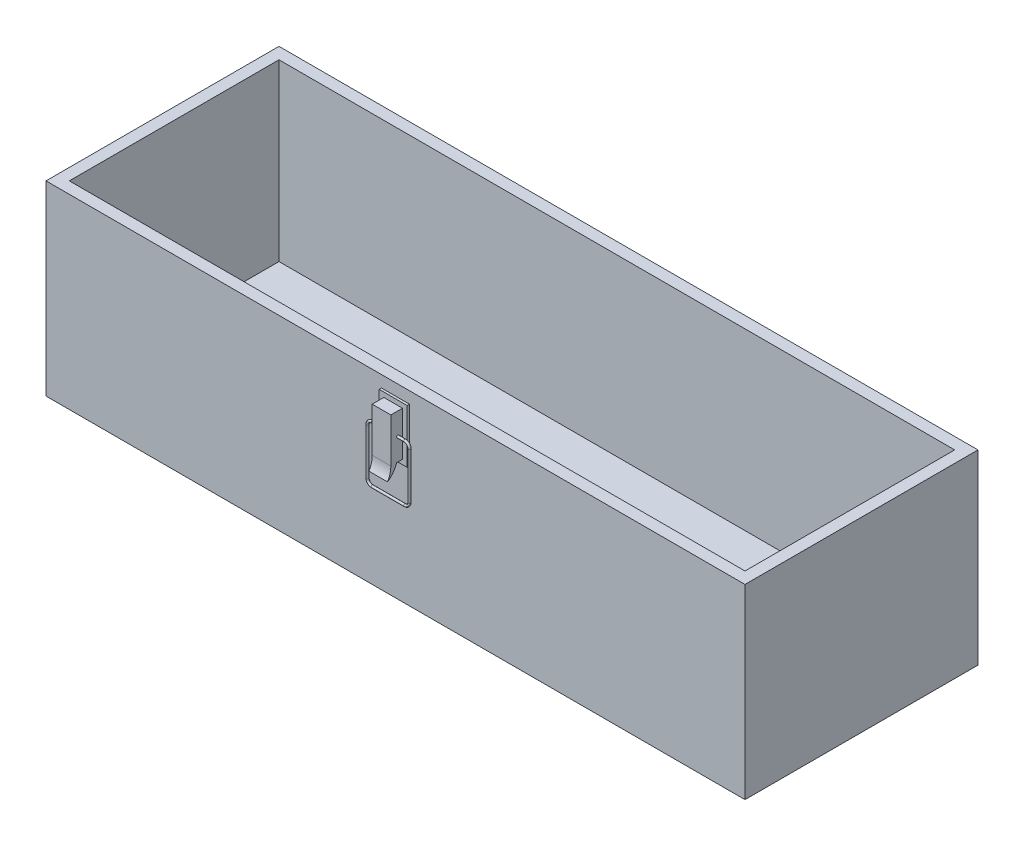
SolidWorks part; units mm, degrees
ref_plane "Front Plane" through (0, 0, 0) normal (0, 0, 1) x (1, 0, 0)
ref_plane "Top Plane" through (0, 0, 0) normal (0, 1, 0) x (1, 0, 0)
ref_plane "Right Plane" through (0, 0, 0) normal (1, 0, 0) x (0, 0, -1)
sketch "Sketch1" plane through (0, 0, 0) normal (0, 1, 0) x (1, 0, 0)
  line L1 (-150, -50) -> (150, -50)
  line L2 (-150, -50) -> (-150, 50)
  line L3 (-150, 50) -> (150, 50)
  line L4 (150, -50) -> (150, 50)
  line L5 (-150, -50) -> (150, 50) construction
  line L6 (-150, 50) -> (150, -50) construction
  point P0 (0, 0)
  dimension "D1" = 300
  dimension "D2" = 100
extrude "Boss-Extrude1" add sketch "Sketch1" along normal blind 80
shell "Shell1" thickness 5
sketch "Sketch2" plane through (0, 0, 50) normal (0, 0, 1) x (1, 0, 0)
  line L0 (0, 0) -> (0, 63.5) construction
  line L1 (-6, 75) -> (6, 75)
  line L2 (-6, 75) -> (-6, 52)
  line L3 (-6, 52) -> (6, 52)
  line L4 (6, 75) -> (6, 52)
  line L5 (-6, 75) -> (6, 52) construction
  line L6 (-6, 52) -> (6, 75) construction
  line L7 (-150, 0) -> (150, 0) construction
  line L8 (-150, 80) -> (150, 80) construction
  point P0 (0, 63.5)
  dimension "D1" = 12
  dimension "D2" = 23
  dimension "D3" = 5
extrude "Boss-Extrude2" add sketch "Sketch2" along normal blind 1
sketch "Sketch3" plane through (0, 0, 51) normal (0, 0, 1) x (1, 0, 0)
  line L8 (4, 54) -> (4, 73)
  line L9 (-4, 54) -> (4, 54)
  line L10 (-4, 73) -> (-4, 54)
  line L11 (4, 73) -> (-4, 73)
  line L12 (4, 54) -> (4, 73)
  line L13 (-4, 54) -> (4, 54)
  line L14 (-4, 73) -> (-4, 54)
  line L15 (4, 73) -> (-4, 73)
  dimension "D1" = 2
extrude "Boss-Extrude3" add sketch "Sketch3" along normal blind 5
sketch "Sketch4" plane through (4, 0, 0) normal (1, 0, 0) x (0, 0, -1)
  line L0 (-56, 54) -> (-56, 73) construction
  line L1 (-56, 54) -> (-51, 54) construction
  line L2 (-56, 54) -> (-53.5, 54)
  arc A0 (-56, 54) -> (-57.3951, 48.7908) centre (-66.4233, 54) cw
  arc A1 (-53.5, 54) -> (-57.3951, 48.7908) centre (-63.3786, 57.3256) cw
extrude "Boss-Extrude4" add sketch "Sketch4" against normal up to surface (8 mm away) up to face at (-4, 63.5, 53.5)
ref_plane "Plane1" through (0, 0, 53) normal (0, 0, 1) x (1, 0, 0)
sketch "Sketch5" plane through (0, 0, 53) normal (0, 0, 1) x (1, 0, 0)
  line L0 (-4, 63.5) -> (-7, 63.5)
  line L1 (-4, 73) -> (-4, 54) construction
  line L2 (-9, 61.5) -> (-9, 41.5)
  line L3 (-7, 39.5) -> (7, 39.5)
  line L4 (9, 41.5) -> (9, 61.5)
  line L5 (7, 63.5) -> (4, 63.5)
  line L6 (4, 54) -> (4, 73) construction
  line L7 (0, 0) -> (0, 39.5) construction
  arc A0 (-9, 41.5) -> (-7, 39.5) centre (-7, 41.5) ccw
  arc A1 (7, 39.5) -> (9, 41.5) centre (7, 41.5) ccw
  arc A2 (9, 61.5) -> (7, 63.5) centre (7, 61.5) ccw
  arc A3 (-7, 63.5) -> (-9, 61.5) centre (-7, 61.5) ccw
  point P15 (-9, 39.5)
  point P18 (9, 39.5)
  point P21 (9, 63.5)
  dimension "D3" = 2
  dimension "D1" = 24
  dimension "D2" = 18
sketch "Sketch6" plane through (-4, 0, 0) normal (-1, 0, 0) x (0, 0, 1)
  circle A0 centre (53, 63.5) radius 0.5
  dimension "D1" = 1
sweep "Sweep1" add profiles "Sketch6" path "Sketch5"
